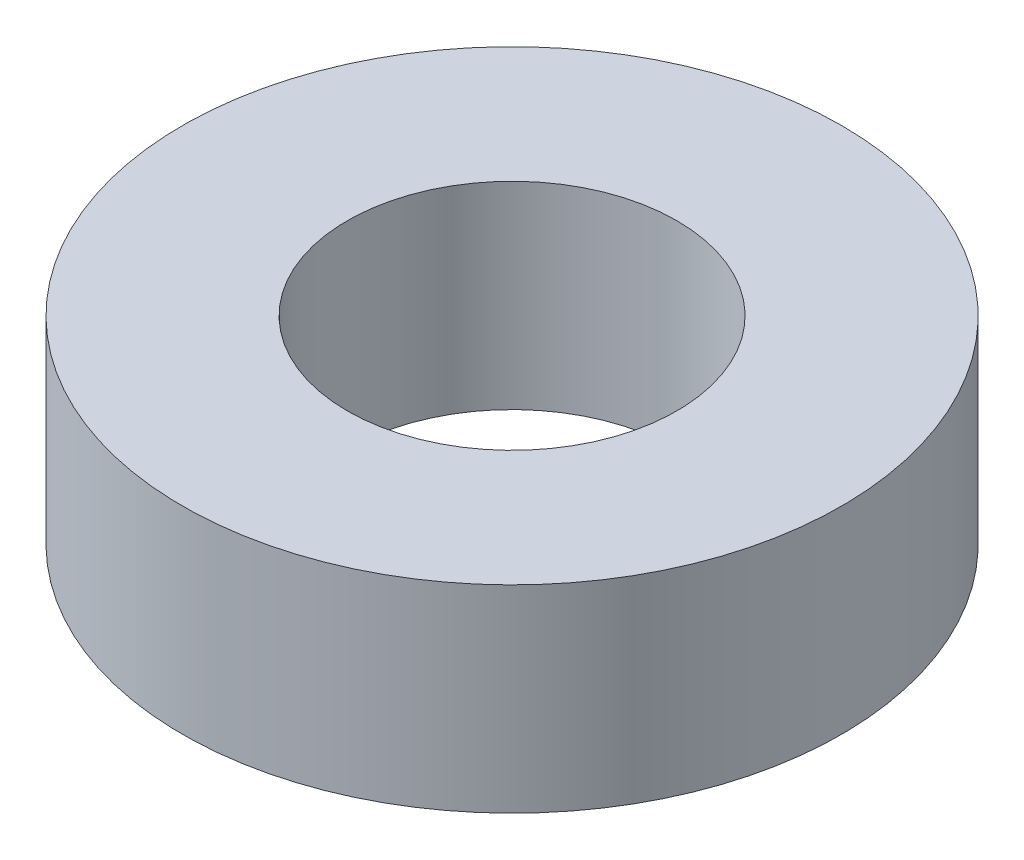
SolidWorks part; units mm, degrees
material "普通碳钢"
ref_plane "前视基准面" through (0, 0, 0) normal (0, 0, 1) x (1, 0, 0)
ref_plane "上视基准面" through (0, 0, 0) normal (0, 1, 0) x (1, 0, 0)
ref_plane "右视基准面" through (0, 0, 0) normal (1, 0, 0) x (0, 0, -1)
sketch "草图1" plane through (0, 0, 0) normal (0, 1, 0) x (1, 0, 0)
  circle A0 centre (0, 0) radius 5
  circle A1 centre (0, 0) radius 2.5
  dimension "D1" = 5
  dimension "D2" = 10
extrude "凸台-拉伸1" add sketch "草图1" along normal mid plane 3
move or copy body "实体-移动/复制1" bodies to move or copy 106
